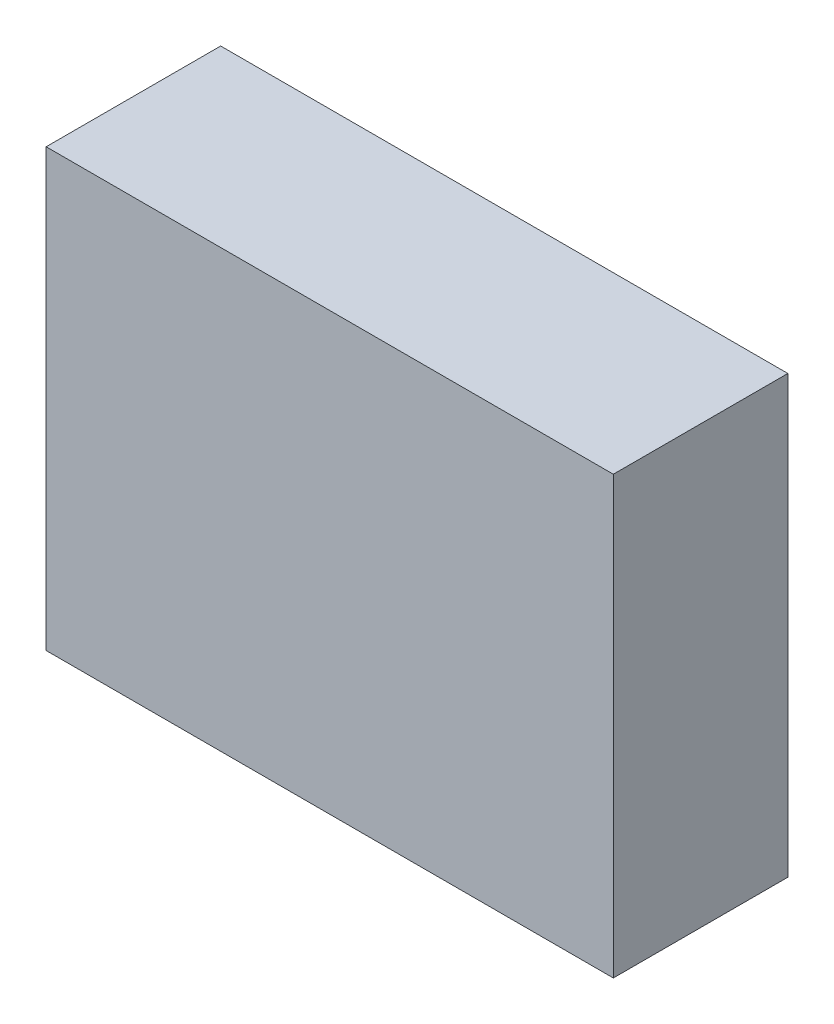
SolidWorks part; units mm, degrees
ref_plane "Front Plane" through (0, 0, 0) normal (0, 0, 1) x (1, 0, 0)
ref_plane "Top Plane" through (0, 0, 0) normal (0, 1, 0) x (1, 0, 0)
ref_plane "Right Plane" through (0, 0, 0) normal (1, 0, 0) x (0, 0, -1)
sketch "Sketch1" plane through (0, 0, 0) normal (0, 1, 0) x (1, 0, 0)
  line L1 (-65, 15.6515) -> (65, 15.6515)
  line L2 (-65, 15.6515) -> (-65, -24.3485)
  line L3 (-65, -24.3485) -> (65, -24.3485)
  line L4 (65, 15.6515) -> (65, -24.3485)
  dimension "D1" = 130
  dimension "D2" = 65
  dimension "D3" = 40
extrude "Boss-Extrude1" add sketch "Sketch1" along normal blind 100
